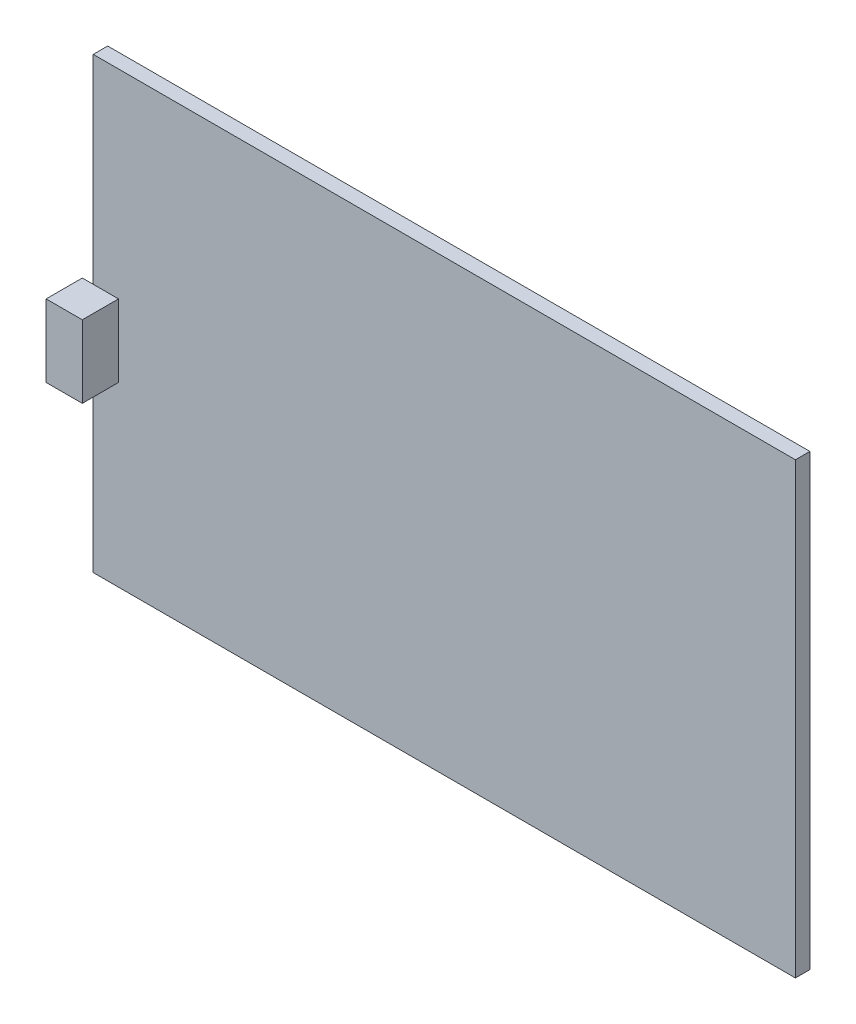
SolidWorks part; units mm, degrees
ref_plane "Plan de face" through (0, 0, 0) normal (0, 0, 1) x (1, 0, 0)
ref_plane "Plan de dessus" through (0, 0, 0) normal (0, 1, 0) x (1, 0, 0)
ref_plane "Plan de droite" through (0, 0, 0) normal (1, 0, 0) x (0, 0, -1)
sketch "Esquisse1" plane through (0, 0, 0) normal (0, 0, 1) x (1, 0, 0)
  line L1 (-48.1177, 23.3333) -> (48.8823, 23.3333)
  line L2 (-48.1177, 23.3333) -> (-48.1177, -38.6667)
  line L3 (-48.1177, -38.6667) -> (48.8823, -38.6667)
  line L4 (48.8823, 23.3333) -> (48.8823, -38.6667)
  dimension "D1" = 62
  dimension "D2" = 97
extrude "Boss.-Extru.1" add sketch "Esquisse1" along normal blind 2
sketch "Esquisse3" plane through (0, 0, 2) normal (0, 0, 1) x (1, 0, 0)
  line L0 (-48.1177, 23.3333) -> (-48.1177, -38.6667) construction
  line L1 (-48.1177, -6.1667) -> (-46.6077, -6.1667)
  line L2 (-48.1177, -6.1667) -> (-48.1177, -9.1667)
  line L3 (-48.1177, -9.1667) -> (-46.6077, -9.1667)
  line L4 (-46.6077, -6.1667) -> (-46.6077, -9.1667)
  line L5 (-48.1177, -6.1667) -> (-48.1177, 23.3333) construction
  line L6 (-48.1177, -9.1667) -> (-48.1177, -38.6667) construction
  dimension "D1" = 1.51
  dimension "D2" = 3
extrude "Boss.-Extru.3" add sketch "Esquisse3" along normal blind 1.51
sketch "Esquisse4" plane through (0, 0, 3.51) normal (0, 0, 1) x (1, 0, 0)
  line L0 (-48.1177, 23.3333) -> (-48.1177, -6.1667) construction
  line L1 (-48.1177, -2.6667) -> (-43.1177, -2.6667)
  line L2 (-48.1177, -2.6667) -> (-48.1177, -12.6667)
  line L3 (-48.1177, -12.6667) -> (-43.1177, -12.6667)
  line L4 (-43.1177, -2.6667) -> (-43.1177, -12.6667)
  line L5 (-47.3627, -6.1667) -> (-47.3627, -2.6667) construction
  line L6 (-46.6077, -6.1667) -> (-48.1177, -6.1667) construction
  line L7 (-47.3627, -9.1667) -> (-47.3627, -12.6667) construction
  line L8 (-48.1177, -9.1667) -> (-46.6077, -9.1667) construction
  dimension "D1" = 10
  dimension "D2" = 5
extrude "Boss.-Extru.4" add sketch "Esquisse4" along normal blind 5
